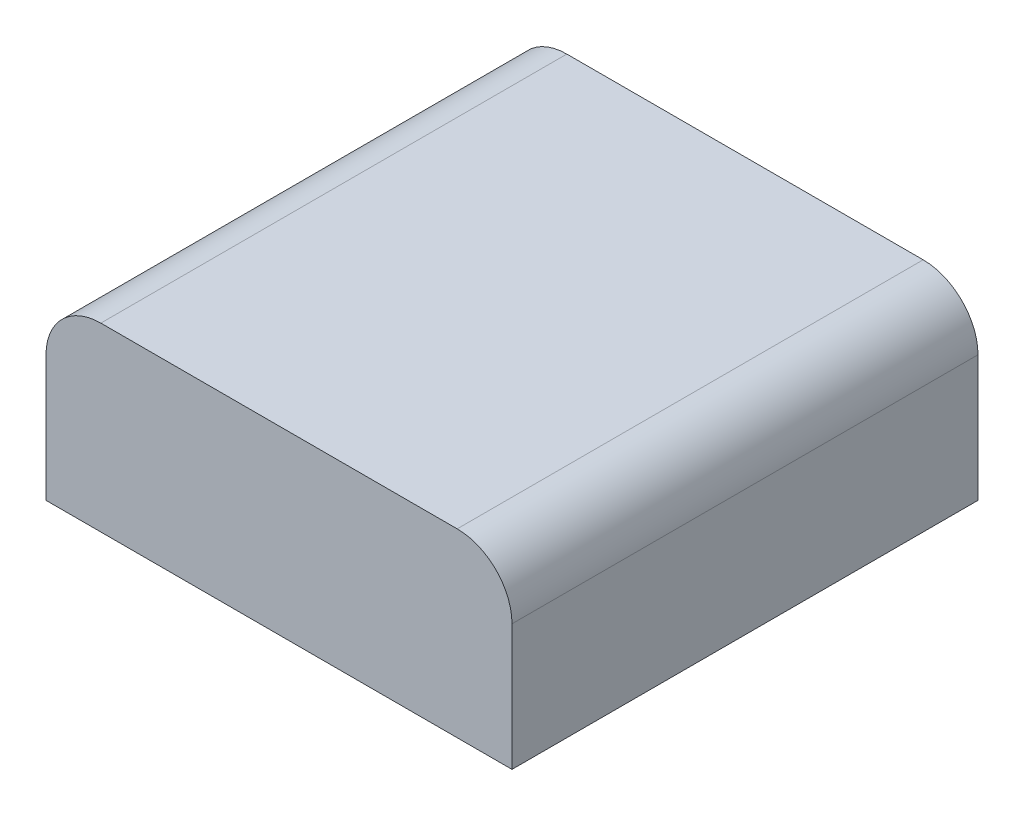
SolidWorks part; units mm, degrees
ref_plane "Front Plane" through (0, 0, 0) normal (0, 0, 1) x (1, 0, 0)
ref_plane "Top Plane" through (0, 0, 0) normal (0, 1, 0) x (1, 0, 0)
ref_plane "Right Plane" through (0, 0, 0) normal (1, 0, 0) x (0, 0, -1)
sketch "Sketch3" plane through (0, 0, 0) normal (0, 0, 1) x (1, 0, 0)
  line L1 (-32.5, 16.5) -> (32.5, 16.5)
  line L2 (-42.5, 6.5) -> (-42.5, -16.5)
  line L3 (-42.5, -16.5) -> (42.5, -16.5)
  line L4 (42.5, 6.5) -> (42.5, -16.5)
  line L5 (-42.5, 16.5) -> (42.5, -16.5) construction
  line L6 (-42.5, -16.5) -> (42.5, 16.5) construction
  arc A0 (42.5, 6.5) -> (32.5, 16.5) centre (32.5, 6.5) ccw
  arc A1 (-42.5, 6.5) -> (-32.5, 16.5) centre (-32.5, 6.5) cw
  point P0 (0, 0)
  dimension "D2" = 10
  dimension "D1" = 85
  dimension "D3" = 33
extrude "Boss-Extrude1" add sketch "Sketch3" along normal mid plane 85
shell "Shell1" thickness 2
